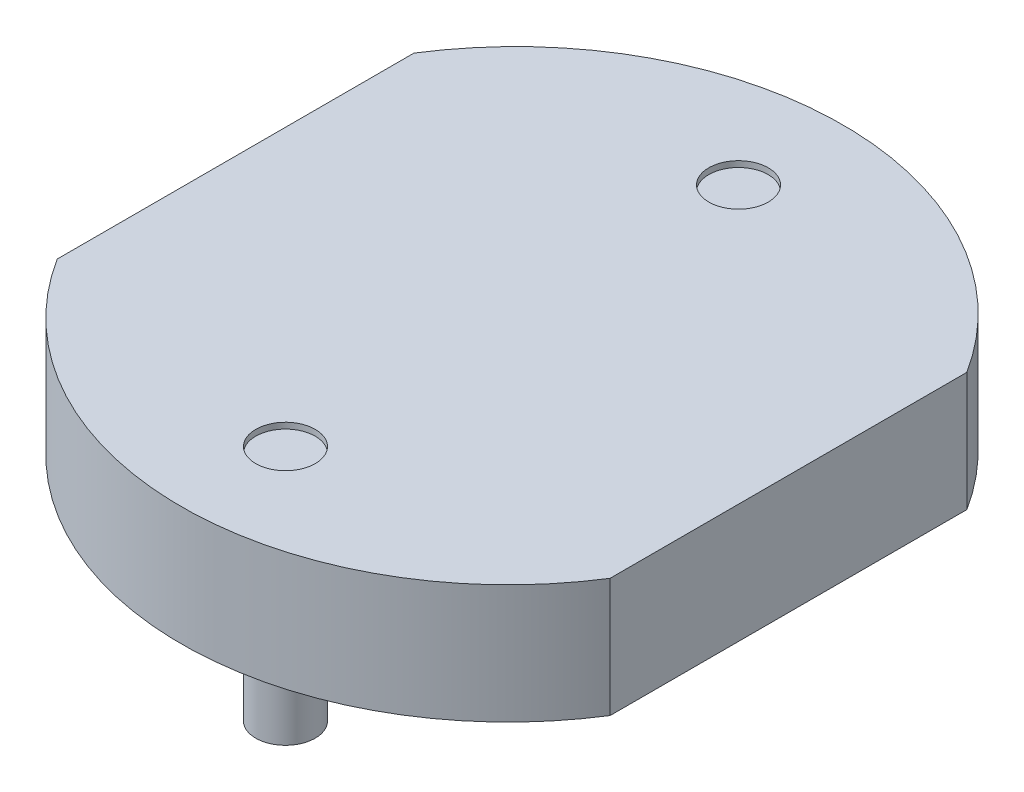
SolidWorks part; units mm, degrees
ref_plane "Front Plane" through (0, 0, 0) normal (0, 0, 1) x (1, 0, 0)
ref_plane "Top Plane" through (0, 0, 0) normal (0, 1, 0) x (1, 0, 0)
ref_plane "Right Plane" through (0, 0, 0) normal (1, 0, 0) x (0, 0, -1)
sketch "Sketch1" plane through (0, 0, 0) normal (0, 1, 0) x (1, 0, 0)
  line L0 (0, 0) -> (0, 3) construction
  line L1 (0, 3) -> (4.65, 3) construction
  line L2 (4.65, 3) -> (0, 3) construction
  line L3 (0, 3) -> (-4.65, 3) construction
  line L4 (0, 0) -> (2.5972, 0) construction
  line L5 (4.65, 3) -> (4.65, -3)
  line L6 (-4.65, 3) -> (-4.65, -3)
  arc A0 (-4.65, 3) -> (4.65, 3) centre (0, 0.0627) cw
  arc A1 (-4.65, -3) -> (4.65, -3) centre (0, -0.0627) ccw
  dimension "D1" = 4.65
  dimension "D3" = 5.5
  dimension "D2" = 4.65
  dimension "D4" = 3
extrude "Base-Extrude" add sketch "Sketch1" along normal blind 2
sketch "Sketch2" plane through (0, 0, 0) normal (0, -1, 0) x (1, 0, 0)
  line L0 (0, 0) -> (0, 3.81) construction
  line L1 (0.1347, 0) -> (2.1996, 0) construction
  circle A0 centre (0, 3.81) radius 0.5
  circle A1 centre (0, -3.81) radius 0.5
  dimension "D2" = 1
  dimension "D1" = 3.81
extrude "Pin-Extrude" add sketch "Sketch2" along normal blind 2
sketch "Sketch3" plane through (0, 2, 0) normal (0, 1, 0) x (1, 0, 0)
  line L0 (0, 0) -> (0, 3.81) construction
  line L1 (0, 0) -> (-0.8304, 0) construction
  circle A0 centre (0, 3.81) radius 0.5
  circle A1 centre (0, -3.81) radius 0.5
  dimension "D2" = 1
  dimension "D1" = 3.81
extrude "Pin-Cut" cut sketch "Sketch3" against normal blind 0.1
equation "\"D1@Sketch1\"=.93/2"
equation "\"D2@Sketch1\"=.93/2"
equation "\"D3@Sketch1\"=1.1/2"
equation "\"D1@Sketch2\"=.762/2"
equation "\"D1@Sketch3\"=.762/2"
